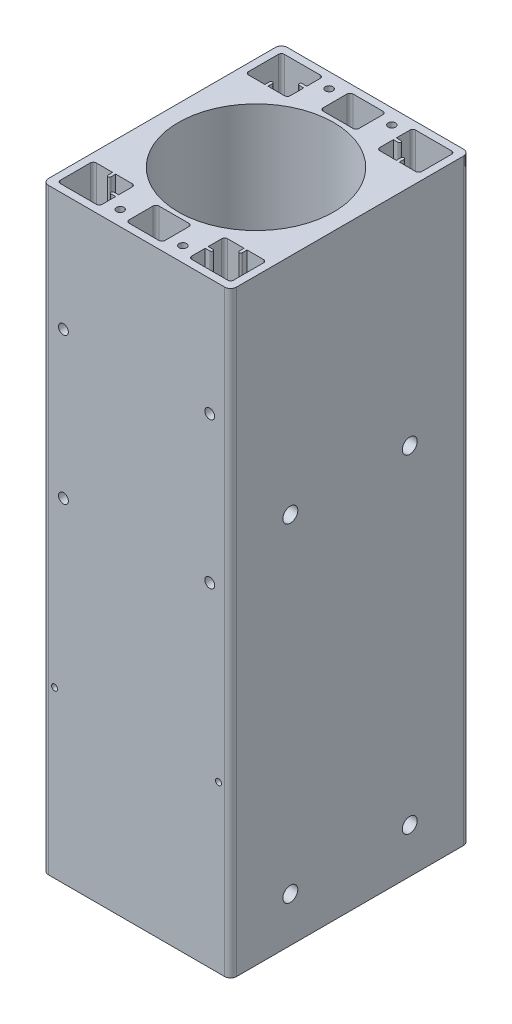
SolidWorks part; units mm, degrees
material "Hliník 3.3547 (EN-AW 5083)"
ref_plane "Přední rovina" through (0, 0, 0) normal (0, 0, 1) x (1, 0, 0)
ref_plane "Horní rovina" through (0, 0, 0) normal (0, 1, 0) x (1, 0, 0)
ref_plane "Pravá rovina" through (0, 0, 0) normal (1, 0, 0) x (0, 0, -1)
sketch "Skica1" plane through (0, 0, 0) normal (0, 1, 0) x (1, 0, 0)
  line L0 (-31.5, -38) -> (-31.5, 38)
  line L1 (31.5, 38) -> (31.5, -38)
  line L2 (29.5, -40) -> (-29.5, -40)
  line L3 (-29.5, 40) -> (29.5, 40)
  line L4 (28, -37.5) -> (16, -37.5)
  line L5 (-16, -37.5) -> (-28, -37.5)
  line L6 (-15, -36.5) -> (-15, -32)
  line L7 (-16, -25.5) -> (-21.5, -25.5)
  line L8 (-29, -36.5) -> (-29, -26.5)
  line L9 (5, -37.5) -> (-5, -37.5)
  line L10 (6, -36.5) -> (6, -28.5)
  line L11 (5, -27.5) -> (-5, -27.5)
  line L12 (-6, -36.5) -> (-6, -28.5)
  line L13 (29, -36.5) -> (29, -26.5)
  line L14 (28, -25.5) -> (22.5, -25.5)
  line L15 (15, -36.5) -> (15, -32)
  line L16 (28, 25.5) -> (22.5, 25.5)
  line L17 (29, 26.5) -> (29, 36.5)
  line L18 (28, 37.5) -> (16, 37.5)
  line L19 (15, 26.5) -> (15, 31)
  line L20 (-16, 25.5) -> (-21.5, 25.5)
  line L21 (-15, 26.5) -> (-15, 31)
  line L22 (-16, 37.5) -> (-28, 37.5)
  line L23 (-29, 26.5) -> (-29, 36.5)
  line L24 (5, 27.5) -> (-5, 27.5)
  line L25 (6, 28.5) -> (6, 36.5)
  line L26 (5, 37.5) -> (-5, 37.5)
  line L27 (-6, 28.5) -> (-6, 36.5)
  line L28 (-22.5, -25.5) -> (-22.5, -27.05)
  line L29 (-21.5, -27.05) -> (-21.5, -25.5)
  line L30 (-15, -31) -> (-16.55, -31)
  line L31 (-16.55, -32) -> (-15, -32)
  line L32 (-22.5, -25.5) -> (-28, -25.5)
  line L33 (-15, -31) -> (-15, -26.5)
  line L34 (15, -31) -> (16.55, -31)
  line L35 (15, -32) -> (16.55, -32)
  line L36 (21.5, -25.5) -> (21.5, -27.05)
  line L37 (22.5, -25.5) -> (22.5, -27.05)
  line L38 (21.5, -25.5) -> (16, -25.5)
  line L39 (15, -31) -> (15, -26.5)
  line L40 (-22.5, 25.5) -> (-22.5, 27.05)
  line L41 (-21.5, 27.05) -> (-21.5, 25.5)
  line L42 (-15, 31) -> (-16.55, 31)
  line L43 (-15, 32) -> (-16.55, 32)
  line L44 (-15, 32) -> (-15, 36.5)
  line L45 (-22.5, 25.5) -> (-28, 25.5)
  line L46 (15, 32) -> (16.55, 32)
  line L47 (16.55, 31) -> (15, 31)
  line L48 (21.5, 25.5) -> (21.5, 27.05)
  line L49 (22.5, 27.05) -> (22.5, 25.5)
  line L50 (21.5, 25.5) -> (16, 25.5)
  line L51 (15, 32) -> (15, 36.5)
  circle A0 centre (0, 0) radius 26
  arc A1 (-29.5, -40) -> (-31.5, -38) centre (-29.5, -38) cw
  arc A2 (-31.5, 38) -> (-29.5, 40) centre (-29.5, 38) cw
  arc A3 (29.5, 40) -> (31.5, 38) centre (29.5, 38) cw
  arc A4 (31.5, -38) -> (29.5, -40) centre (29.5, -38) cw
  arc A5 (29, 36.5) -> (28, 37.5) centre (28, 36.5) ccw
  arc A6 (28, 25.5) -> (29, 26.5) centre (28, 26.5) ccw
  arc A7 (16, 25.5) -> (15, 26.5) centre (16, 26.5) cw
  arc A8 (16, 37.5) -> (15, 36.5) centre (16, 36.5) ccw
  arc A9 (-15, 36.5) -> (-16, 37.5) centre (-16, 36.5) ccw
  arc A10 (-16, 25.5) -> (-15, 26.5) centre (-16, 26.5) ccw
  arc A11 (-28, 25.5) -> (-29, 26.5) centre (-28, 26.5) cw
  arc A12 (-28, 37.5) -> (-29, 36.5) centre (-28, 36.5) ccw
  arc A13 (28, -37.5) -> (29, -36.5) centre (28, -36.5) ccw
  arc A14 (29, -26.5) -> (28, -25.5) centre (28, -26.5) ccw
  arc A15 (16, -25.5) -> (15, -26.5) centre (16, -26.5) ccw
  arc A16 (16, -37.5) -> (15, -36.5) centre (16, -36.5) cw
  arc A17 (-16, -37.5) -> (-15, -36.5) centre (-16, -36.5) ccw
  arc A18 (-15, -26.5) -> (-16, -25.5) centre (-16, -26.5) ccw
  arc A19 (-28, -25.5) -> (-29, -26.5) centre (-28, -26.5) ccw
  arc A20 (-28, -37.5) -> (-29, -36.5) centre (-28, -36.5) cw
  arc A21 (5, -37.5) -> (6, -36.5) centre (5, -36.5) ccw
  arc A22 (6, -28.5) -> (5, -27.5) centre (5, -28.5) ccw
  arc A23 (-5, -27.5) -> (-6, -28.5) centre (-5, -28.5) ccw
  arc A24 (-5, -37.5) -> (-6, -36.5) centre (-5, -36.5) cw
  arc A25 (5, 27.5) -> (6, 28.5) centre (5, 28.5) ccw
  arc A26 (6, 36.5) -> (5, 37.5) centre (5, 36.5) ccw
  arc A27 (-5, 37.5) -> (-6, 36.5) centre (-5, 36.5) ccw
  arc A28 (-5, 27.5) -> (-6, 28.5) centre (-5, 28.5) cw
  arc A29 (-22.5, -27.05) -> (-21.5, -27.05) centre (-22, -27.05) ccw
  arc A30 (-16.55, -31) -> (-16.55, -32) centre (-16.55, -31.5) ccw
  arc A31 (22.5, -27.05) -> (21.5, -27.05) centre (22, -27.05) cw
  arc A32 (16.55, -32) -> (16.55, -31) centre (16.55, -31.5) ccw
  arc A33 (-22.5, 27.05) -> (-21.5, 27.05) centre (-22, 27.05) cw
  arc A34 (-16.55, 32) -> (-16.55, 31) centre (-16.55, 31.5) ccw
  arc A35 (16.55, 32) -> (16.55, 31) centre (16.55, 31.5) cw
  arc A36 (21.5, 27.05) -> (22.5, 27.05) centre (22, 27.05) cw
  dimension "D1" = 1
  dimension "D2" = 1
extrude "Přidat vysunutím2" add sketch "Skica1" along normal blind 200
hole_wizard "M6 závit1" positions "Skica5" profile "Skica4" tap size "M6" standard "ISO"
sketch "Skica5" plane through (0, 0, -40) normal (0, 0, -1) x (-1, 0, 0)
  line L0 (-29.5, 0) -> (29.5, 0) construction
  point P0 (-11, 13)
  point P3 (0, 0)
  point P6 (0, 0)
  dimension "D1" = 13
  dimension "D2" = 11
sketch "Skica4" plane through (11, 13, -40) normal (1, 0, 0) x (0, 1, 0)
  line L0 (0, 0) -> (0, 17.5022)
  line L1 (0, 17.5022) -> (2.5, 16)
  line L2 (2.5, 16) -> (2.5, 0.525)
  line L3 (2.5, 0.525) -> (3.025, 0)
  line L5 (3.025, 0) -> (0, 0)
  line L6 (-2.5, 0.525) -> (-3.025, 0) construction
  line L10 (0, 17.5022) -> (-2.5, 16) construction
  line L11 (0, -6.35) -> (0, 107.95) construction
  dimension "Průměr závitníku" = 5
  dimension "Hloubka závitníku" = 16
  dimension "Průměr blíz. kuž. zahloubení" = 6.05
  dimension "Úhel blíz. kuž. zahloubení" = 90
  dimension "Úhel vrtání" = 118
cosmetic thread "Závit díry1" parameters "D1"=12, "D2"=6
pattern_linear "LinPole1" count 2 spacing 22 along (-1, 0, 0) count 2 spacing 110 along (0, 1, 0) of "M6 závit1"
sketch "Skica6" plane through (0, 200, 0) normal (0, 1, 0) x (1, 0, 0)
  line L0 (-26.5, 19.5) -> (26.5, 19.5) construction
  line L1 (26.5, 19.5) -> (26.5, -19.5) construction
  line L2 (26.5, -19.5) -> (-26.5, -19.5) construction
  line L3 (-26.5, -19.5) -> (-26.5, 19.5) construction
  line L4 (0, 0) -> (0, 19.5) construction
  line L5 (0, 0) -> (26.5, 0) construction
  line L6 (-10.5, 35) -> (-10.5, -35) construction
  line L7 (-10.5, -35) -> (10.5, -35) construction
  line L8 (10.5, -35) -> (10.5, 35) construction
  line L9 (10.5, 35) -> (-10.5, 35) construction
  line L11 (-10.5, 0) -> (0, 0) construction
  line L12 (0, 0) -> (0, -35) construction
hole_wizard "M4 závit2" positions "Skica10" profile "Skica9" tap size "M4" standard "ISO"
sketch "Skica10" plane through (0, 0, 0) normal (0, -1, 0) x (-1, 0, 0)
  point P0 (26.5, 19.5)
sketch "Skica9" plane through (-26.5, 0, -19.5) normal (1, 0, 0) x (0, 0, -1)
  line L0 (0, 0) -> (0, 12.4914)
  line L1 (0, 12.4914) -> (1.65, 11.5)
  line L2 (1.65, 11.5) -> (1.65, 0.375)
  line L3 (1.65, 0.375) -> (2.025, 0)
  line L5 (2.025, 0) -> (0, 0)
  line L6 (-1.65, 0.375) -> (-2.025, 0) construction
  line L10 (0, 12.4914) -> (-1.65, 11.5) construction
  line L11 (0, -6.35) -> (0, 107.95) construction
  dimension "Průměr závitníku" = 3.3
  dimension "Hloubka závitníku" = 11.5
  dimension "Průměr blíz. kuž. zahloubení" = 4.05
  dimension "Úhel blíz. kuž. zahloubení" = 90
  dimension "Úhel vrtání" = 118
cosmetic thread "Závit díry3" parameters "D1"=8, "D2"=4
pattern_linear "LinPole3" count 2 spacing 53 along (1, 0, 0) count 2 spacing 39 along (0, 0, 1) of "M4 závit2"
hole_wizard "M4 závit3" positions "Skica12" profile "Skica11" tap size "M4" standard "ISO"
sketch "Skica12" plane through (0, 0, 40) normal (0, 0, 1) x (1, 0, 0)
  line L0 (-29.5, 0) -> (29.5, 0) construction
  point P0 (-24.5, 111.75)
  dimension "D1" = 111.75
  dimension "D2" = 24.5
sketch "Skica11" plane through (-24.5, 111.75, 40) normal (1, 0, 0) x (0, -1, 0)
  line L0 (0, 0) -> (0, 12.4914)
  line L1 (0, 12.4914) -> (1.65, 11.5)
  line L2 (1.65, 11.5) -> (1.65, 0)
  line L5 (1.65, 0) -> (0, 0)
  line L10 (0, 12.4914) -> (-1.65, 11.5) construction
  line L11 (0, -6.35) -> (0, 107.95) construction
  dimension "Průměr závitníku" = 3.3
  dimension "Hloubka závitníku" = 11.5
  dimension "Úhel vrtání" = 118
cosmetic thread "Závit díry4" parameters "D1"=2.5, "D2"=4
pattern_linear "LinPole4" count 2 spacing 49 along (1, 0, 0) count 2 spacing 49 along (0, 1, 0) of "M4 závit3"
hole_wizard "M6 závit2" positions "Skica14" profile "Skica13" tap size "M6" standard "ISO"
sketch "Skica14" plane through (31.5, 0, 0) normal (1, 0, 0) x (0, 0, -1)
  line L0 (-38, 0) -> (38, 0) construction
  point P0 (20, 15)
  point P5 (0, 0)
  dimension "D1" = 15
  dimension "D2" = 20
sketch "Skica13" plane through (31.5, 15, -20) normal (0, 1, 0) x (0, 0, -1)
  line L0 (0, 0) -> (0, 18.5022)
  line L1 (0, 18.5022) -> (2.5, 17)
  line L2 (2.5, 17) -> (2.5, 0)
  line L5 (2.5, 0) -> (0, 0)
  line L10 (0, 18.5022) -> (-2.5, 17) construction
  line L11 (0, -6.35) -> (0, 107.95) construction
  dimension "Průměr závitníku" = 5
  dimension "Hloubka závitníku" = 17
  dimension "Úhel vrtání" = 118
cosmetic thread "Závit díry5" parameters "D1"=12, "D2"=6
pattern_linear "LinPole5" count 2 spacing 110 along (0, 1, 0) count 2 spacing 40 along (0, 0, 1) of "M6 závit2"
hole_wizard "M3 závit1" positions "Skica16" profile "Skica15" tap size "M3" standard "ISO"
sketch "Skica16" plane through (0, 200, 0) normal (0, 1, 0) x (1, 0, 0)
  point P0 (-10.5, -35)
sketch "Skica15" plane through (-10.5, 200, 35) normal (1, 0, 0) x (0, 0, 1)
  line L0 (0, 0) -> (0, 9.2511)
  line L1 (0, 9.2511) -> (1.25, 8.5)
  line L2 (1.25, 8.5) -> (1.25, 0)
  line L5 (1.25, 0) -> (0, 0)
  line L10 (0, 9.2511) -> (-1.25, 8.5) construction
  line L11 (0, -6.35) -> (0, 107.95) construction
  dimension "Průměr závitníku" = 2.5
  dimension "Hloubka závitníku" = 8.5
  dimension "Úhel vrtání" = 118
cosmetic thread "Závit díry6" parameters "D1"=6, "D2"=3
pattern_linear "LinPole6" count 2 spacing 21 along (1, 0, 0) count 2 spacing 70 along (0, 0, -1) of "M3 závit1"
hole_wizard "Ø2.0 (2) průměr díry1" positions "Skica18" profile "Skica17" hole size "Ø2.0" standard "ANSI Metric"
sketch "Skica18" plane through (0, 0, 40) normal (0, 0, 1) x (1, 0, 0)
  point P0 (-27.4475, 55.3724)
  point P3 (27.4235, 55.3724)
sketch "Skica17" plane through (-27.4475, 55.3724, 40) normal (1, 0, 0) x (0, -1, 0)
  line L0 (0, 0) -> (0, 5.6009)
  line L1 (0, 5.6009) -> (1, 5)
  line L2 (1, 5) -> (1, 0)
  line L5 (1, 0) -> (0, 0)
  line L10 (0, 5.6009) -> (-1, 5) construction
  line L11 (0, -6.35) -> (0, 107.95) construction
  dimension "Průměr díry" = 2
  dimension "Hloubka díry" = 5
  dimension "Úhel vrtání" = 118
